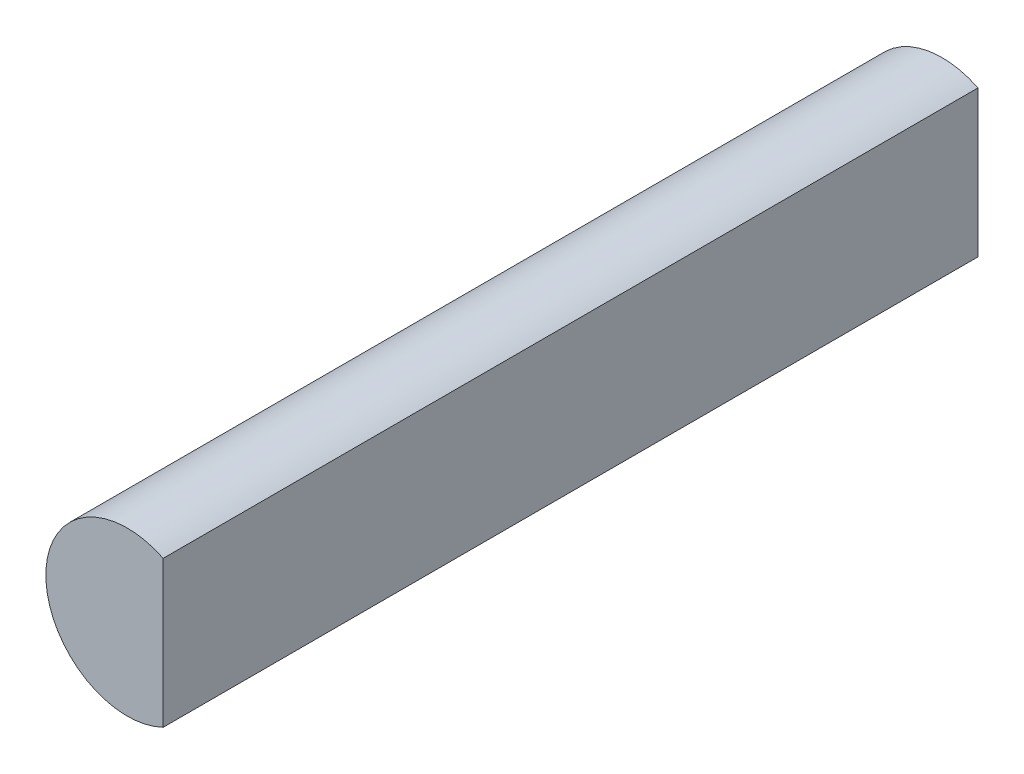
SolidWorks part; units mm, degrees
ref_plane "前视基准面" through (0, 0, 0) normal (0, 0, 1) x (1, 0, 0)
ref_plane "上视基准面" through (0, 0, 0) normal (0, 1, 0) x (1, 0, 0)
ref_plane "右视基准面" through (0, 0, 0) normal (1, 0, 0) x (0, 0, -1)
sketch "草图1" plane through (0, 0, 0) normal (0, 0, 1) x (1, 0, 0)
  line L0 (0.44, 0.898) -> (0.44, -0.898)
  arc A0 (0.44, 0.898) -> (0.44, -0.898) centre (0, 0) ccw
  dimension "D1" = 2
  dimension "D2" = 0.44
extrude "凸台-拉伸1" add sketch "草图1" along normal blind 10
